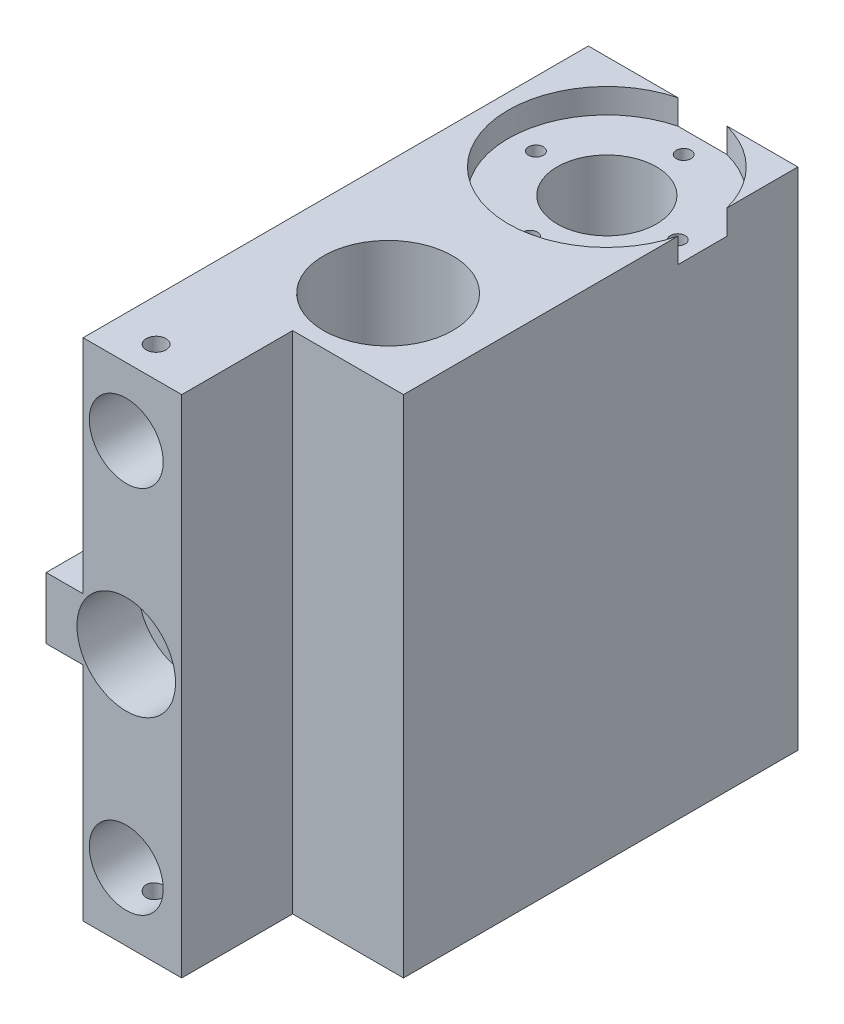
SolidWorks part; units mm, degrees
material "1060 Alloy"
ref_plane "Front Plane" through (0, 0, 0) normal (0, 0, 1) x (1, 0, 0)
ref_plane "Top Plane" through (0, 0, 0) normal (0, 1, 0) x (1, 0, 0)
ref_plane "Right Plane" through (0, 0, 0) normal (1, 0, 0) x (0, 0, -1)
sketch "Sketch1" plane through (0, 0, 0) normal (0, 0, 1) x (1, 0, 0)
  line L0 (-27, -6.0963) -> (-27, -75.9037) construction
  line L1 (0, 0) -> (-40, 0)
  line L2 (0, 0) -> (0, -82)
  line L3 (0, -82) -> (-40, -82)
  line L4 (-40, 0) -> (-40, -82)
  circle A0 centre (-27, -41) radius 5.5
  circle A1 centre (-27, -11) radius 6
  circle A2 centre (-27, -71) radius 6
  dimension "D3" = 11
  dimension "D4" = 12
  dimension "D5" = 12
  dimension "D1" = 40
  dimension "D2" = 82
  dimension "D6" = 11
  dimension "D7" = 30
  dimension "D8" = 13
  dimension "D9" = 30
  dimension "D10" = 11
extrude "Boss-Extrude1" add sketch "Sketch1" along normal blind 12
sketch "Sketch2" plane through (0, 0, 0) normal (0, 0, -1) x (-1, 0, 0)
  line L0 (0, -82) -> (0, 0) construction
  line L1 (40, -82) -> (0, -82) construction
  line L2 (40, 0) -> (40, -82) construction
  line L3 (0, 0) -> (40, 0) construction
  line L4 (0, -82) -> (0, 0)
  line L5 (40, -82) -> (0, -82)
  line L6 (40, 0) -> (40, -82)
  line L7 (0, 0) -> (40, 0)
  circle A0 centre (27, -41) radius 5.5 construction
  circle A1 centre (27, -41) radius 5.5
extrude "Boss-Extrude2" add sketch "Sketch2" along normal blind 70
sketch "Sketch3" plane through (0, 0, 0) normal (0, 1, 0) x (1, 0, 0)
  line L0 (-40, -5) -> (0, -5) construction
  line L1 (-40, -12) -> (-40, 70) construction
  line L2 (0, -12) -> (0, 70) construction
  line L3 (0, -12) -> (-40, -12) construction
  circle A0 centre (-27.1548, -7) radius 1.6
  dimension "D1" = 3.2
  dimension "D2" = 5
  dimension "D3" = 13
extrude "Cut-Extrude1" cut sketch "Sketch3" against normal blind 10
sketch "Sketch4" plane through (0, -82, 0) normal (0, -1, 0) x (1, 0, 0)
  circle A1 centre (-27.1548, 7) radius 1.6
  circle A2 centre (-27.1548, 7) radius 1.6
  dimension "D1" = 0
extrude "Cut-Extrude2" cut sketch "Sketch4" against normal blind 10
sketch "Sketch5" plane through (0, 0, 0) normal (0, 1, 0) x (1, 0, 0)
  line L0 (-15.5, 70) -> (-15.5, 49) construction
  line L1 (-40, 70) -> (0, 70) construction
  line L2 (0, -12) -> (-40, -12) construction
  line L3 (0, -12) -> (0, 70) construction
  line L4 (-15.5, 60) -> (-15.5, 49) construction
  line L5 (-15.5, 29.5) -> (-15.5, -12) construction
  line L6 (-15.5, 29.5) -> (-15.5, 8.5) construction
  circle A1 centre (-15.5, 19) radius 10.5
  circle A2 centre (-15.5, 54.5) radius 5.5
  dimension "D2" = 11
  dimension "D3" = 25
  dimension "D4" = 21
  dimension "D1" = 15.5
  dimension "D6" = 51
extrude "Cut-Extrude3" cut sketch "Sketch5" against normal blind 100
sketch "Sketch6" plane through (0, 0, 0) normal (0, 1, 0) x (1, 0, 0)
  circle A0 centre (-15.5, 54.5) radius 16
  dimension "D1" = 32
extrude "Cut-Extrude4" cut sketch "Sketch6" against normal blind 4
sketch "Sketch19" plane through (0, -4, 0) normal (0, 1, 0) x (1, 0, 0)
  circle A0 centre (-15.5, 54.5) radius 8.05
  dimension "D1" = 16.1
extrude "Cut-Extrude17" cut sketch "Sketch19" against normal blind 16
sketch "Sketch12" plane through (0, -4, 0) normal (0, 1, 0) x (1, 0, 0)
  line L1 (-3.5097, 54.0181) -> (-3.0278, 66.0084) construction
  line L2 (-3.0278, 66.0084) -> (-15.0181, 66.4903) construction
  line L3 (-27.4903, 54.9819) -> (-27.9722, 42.9916) construction
  line L4 (-27.9722, 42.9916) -> (-15.9819, 42.5097) construction
  circle A0 centre (-15.5, 54.5) radius 12 construction
  circle A1 centre (-15.9819, 42.5097) radius 1.2
  circle A2 centre (-3.5097, 54.0181) radius 1.2
  circle A3 centre (-15.0181, 66.4903) radius 1.2
  circle A4 centre (-27.4903, 54.9819) radius 1.2
  dimension "D1" = 24
  dimension "D2" = 2.4
extrude "Cut-Extrude12" cut sketch "Sketch12" against normal blind 12
sketch "Sketch13" plane through (0, 0, -70) normal (0, 0, -1) x (-1, 0, 0)
  line L1 (40, 0) -> (60, 0)
  line L2 (40, 0) -> (40, -70)
  line L3 (40, -70) -> (60, -70)
  line L4 (60, 0) -> (60, -70)
  dimension "D1" = 20
  dimension "D2" = 70
extrude "Boss-Extrude3" add sketch "Sketch13" against normal blind 30
sketch "Sketch14" plane through (0, 0, -70) normal (0, 0, -1) x (-1, 0, 0)
  line L1 (50.54, -17.46) -> (27, -17.46) construction
  line L2 (3.46, -41) -> (3.46, -64.54) construction
  line L3 (3.46, -64.54) -> (27, -64.54) construction
  line L4 (50.54, -41) -> (50.54, -17.46) construction
  circle A0 centre (27, -41) radius 23.54 construction
  circle A1 centre (50.54, -41) radius 2
  circle A2 centre (27, -17.46) radius 2
  circle A3 centre (3.46, -41) radius 2
  circle A4 centre (27, -64.54) radius 2
  dimension "D1" = 47.08
  dimension "D2" = 4
extrude "Cut-Extrude13" cut sketch "Sketch14" against normal blind 12
sketch "Sketch15" plane through (0, 0, -70) normal (0, 0, -1) x (-1, 0, 0)
  line L0 (34, 0) -> (34, -36)
  line L1 (60, 0) -> (19.4686, 0) construction
  line L2 (34, -36) -> (54.5811, -36)
  line L4 (34, -82) -> (34, -46)
  line L5 (0, -82) -> (40, -82) construction
  line L6 (34, -46) -> (54.5811, -46)
  line L7 (54.5811, -46) -> (54.5811, -36)
  line L8 (34, 0) -> (77.5206, 0)
  line L9 (77.5206, 0) -> (77.5206, -82)
  line L10 (77.5206, -82) -> (34, -82)
  line L11 (60, -70) -> (60, 0) construction
  dimension "D1" = 26
  dimension "D2" = 10
  dimension "D3" = 36
extrude "Cut-Extrude14" cut sketch "Sketch15" against normal blind 115
sketch "Sketch18" plane through (0, 0, -70) normal (0, 0, -1) x (-1, 0, 0)
  circle A0 centre (27, -41) radius 19.1
  dimension "D1" = 38.2
extrude "Cut-Extrude16" cut sketch "Sketch18" against normal blind 2
sketch "Sketch20" plane through (0, -82, 0) normal (0, -1, 0) x (1, 0, 0)
  line L1 (0, 12) -> (-18, 12)
  line L2 (0, 12) -> (0, -6)
  line L3 (0, -6) -> (-18, -6)
  line L4 (-18, 12) -> (-18, -6)
  dimension "D1" = 18
  dimension "D2" = 18
extrude "Cut-Extrude18" cut sketch "Sketch20" against normal blind 100
sketch "Sketch21" plane through (0, 0, 12) normal (0, 0, 1) x (1, 0, 0)
  circle A0 centre (-27, -41) radius 8
  dimension "D1" = 16
extrude "Cut-Extrude19" cut sketch "Sketch21" against normal blind 10
